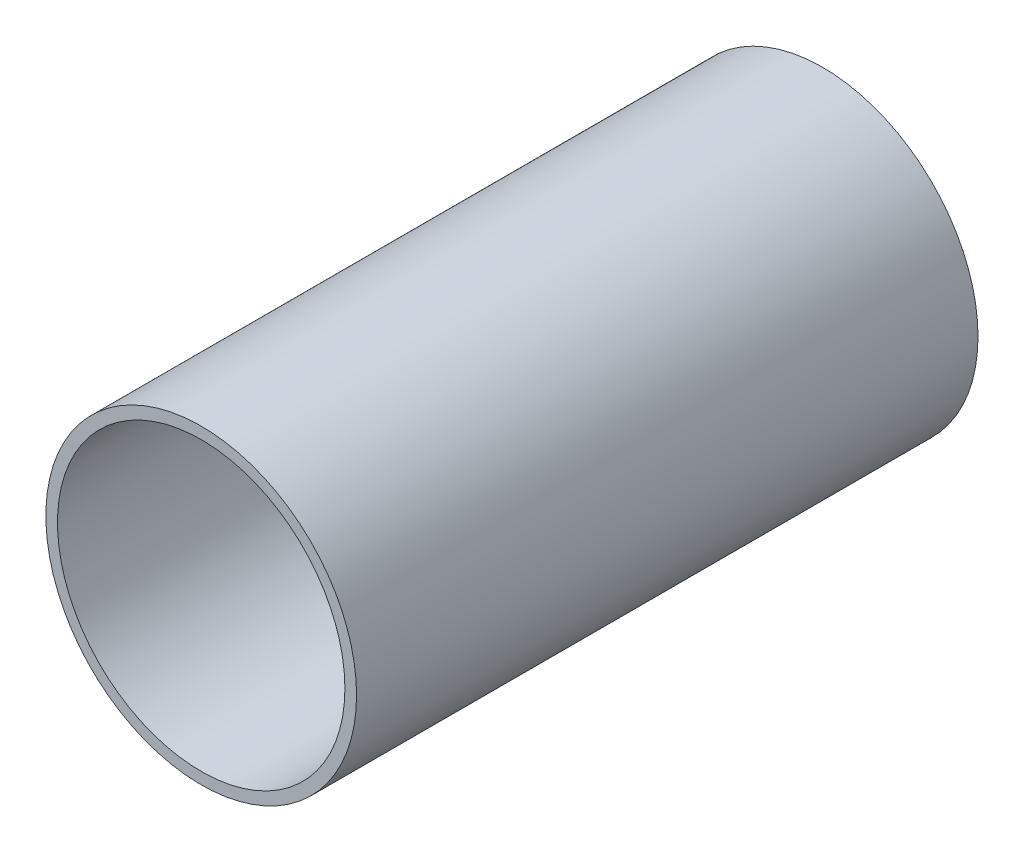
SolidWorks part; units mm, degrees
material "电镀钢"
ref_plane "前视基准面" through (0, 0, 0) normal (0, 0, 1) x (1, 0, 0)
ref_plane "上视基准面" through (0, 0, 0) normal (0, 1, 0) x (1, 0, 0)
ref_plane "右视基准面" through (0, 0, 0) normal (1, 0, 0) x (0, 0, -1)
other "Configuration Table"
sketch "草图1" plane through (0, 0, 0) normal (0, 0, 1) x (1, 0, 0)
  circle A0 centre (0, 14.6834) radius 200
  dimension "D1" = 400
extrude "凸台-拉伸1" add sketch "草图1" along normal blind 800
sketch "草图2" plane through (0, 0, 800) normal (0, 0, 1) x (1, 0, 0)
  circle A0 centre (0, 14.6834) radius 185
  circle A1 centre (0, 14.6834) radius 200 construction
  dimension "D1" = 370
extrude "切除-拉伸2" cut sketch "草图2" against normal blind 800 contours A0
